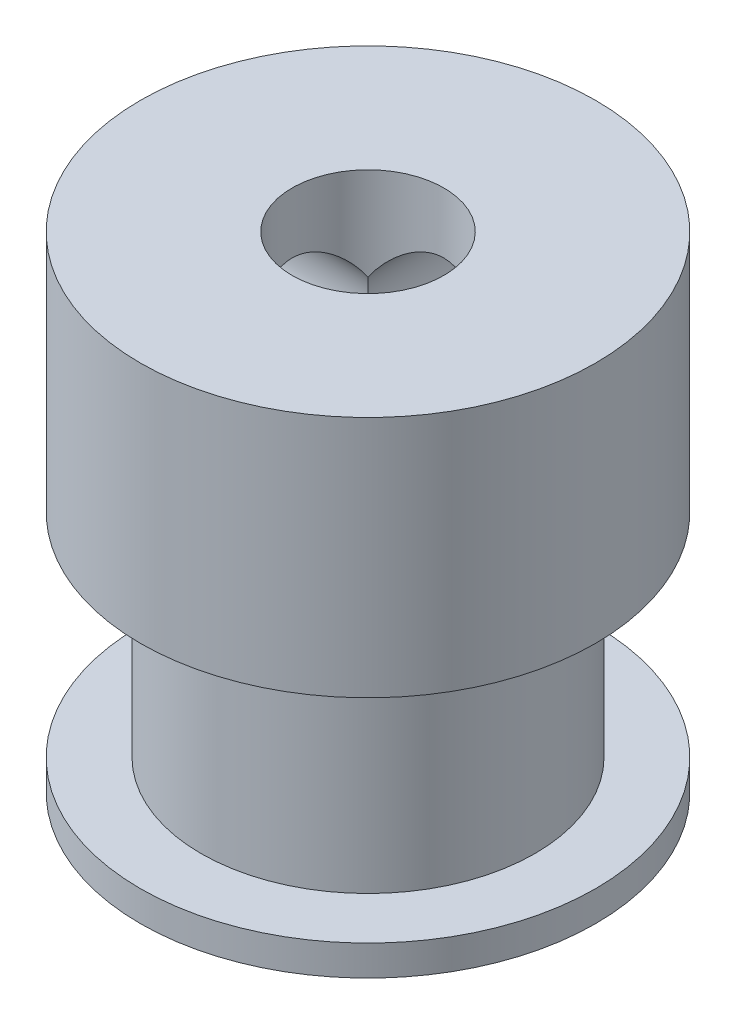
SolidWorks part; units mm, degrees
ref_plane "Plan de face" through (0, 0, 0) normal (0, 0, 1) x (1, 0, 0)
ref_plane "Plan de dessus" through (0, 0, 0) normal (0, 1, 0) x (1, 0, 0)
ref_plane "Plan de droite" through (0, 0, 0) normal (1, 0, 0) x (0, 0, -1)
sketch "Esquisse1" plane through (0, 0, 0) normal (0, 1, 0) x (1, 0, 0)
  circle A0 centre (0, 0) radius 7.5
  dimension "D1" = 15
extrude "Boss.-Extru.1" add sketch "Esquisse1" along normal blind 16
sketch "Esquisse2" plane through (0, 0, 0) normal (1, 0, 0) x (0, 0, -1)
  line L0 (-7.5, 16) -> (-7.5, 0) construction
  line L1 (-7.5, 8) -> (-5.5, 8)
  line L2 (-7.5, 8) -> (-7.5, 1)
  line L3 (-7.5, 1) -> (-5.5, 1)
  line L4 (-5.5, 8) -> (-5.5, 1)
  line L6 (-7.5, 0) -> (7.5, 0) construction
  line L7 (0, 0) -> (0, 18.3319) construction
  dimension "D1" = 7
  dimension "D2" = 1
  dimension "D3" = 2
revolve "Enlèvement de matière-Révolution1" cut sketch "Esquisse2" angle 360 about L7
sketch "Esquisse3" plane through (0, 16, 0) normal (0, 1, 0) x (1, 0, 0)
  circle A0 centre (0, 0) radius 2.5
  dimension "D1" = 5
extrude "Enlèv. mat.-Extru.1" cut sketch "Esquisse3" against normal blind 16
sketch "Esquisse4" plane through (0, 0, 0) normal (0, 0, 1) x (1, 0, 0)
  line L0 (7.5, 16) -> (-7.5, 16) construction
  circle A0 centre (0, 12) radius 2
  point P4 (0, 0)
  dimension "D1" = 4
  dimension "D2" = 4
extrude "Enlèv. mat.-Extru.2" cut sketch "Esquisse4" against normal through all
pattern_circular "Répétition circulaire1" count 2 over 90 about axis through (0, 16, 0) along (0, -1, 0) of "Enlèv. mat.-Extru.2"
